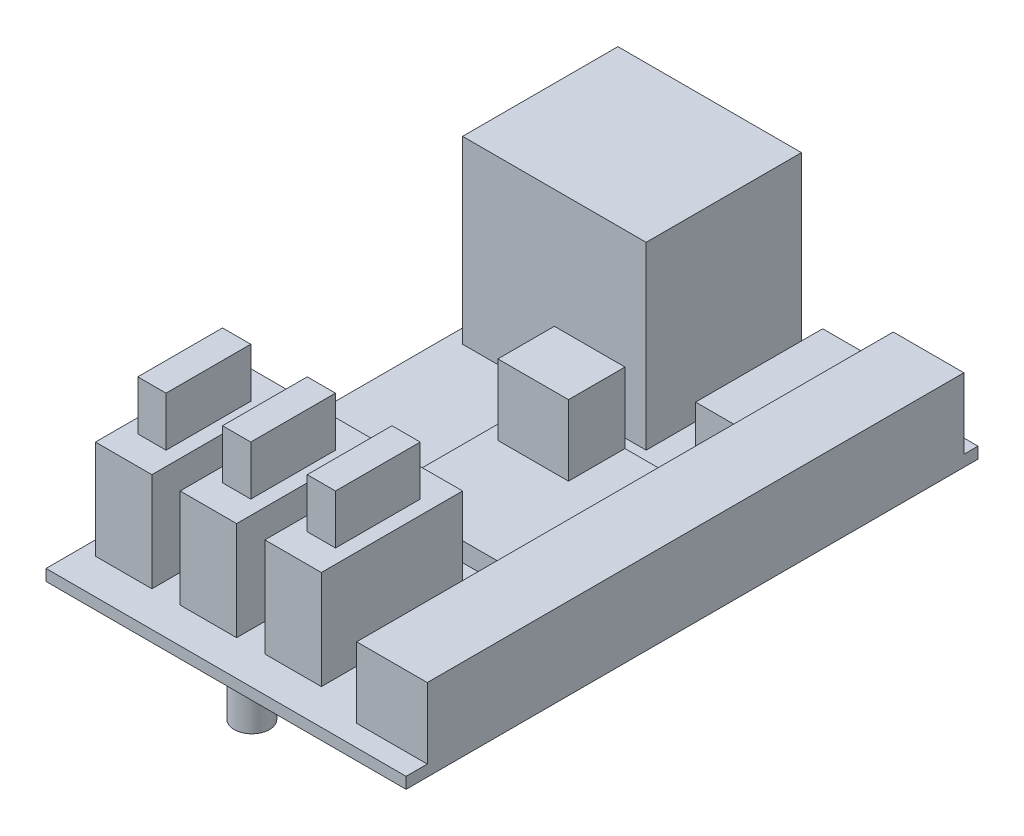
SolidWorks part; units mm, degrees
ref_plane "Front Plane" through (0, 0, 0) normal (0, 0, 1) x (1, 0, 0)
ref_plane "Top Plane" through (0, 0, 0) normal (0, 1, 0) x (1, 0, 0)
ref_plane "Right Plane" through (0, 0, 0) normal (1, 0, 0) x (0, 0, -1)
sketch "SK_P01_Standoff" plane through (0, 0, 0) normal (0, 1, 0) x (1, 0, 0)
  circle A0 centre (0, 36.85) radius 2.5
extrude "P01_Standoff" add sketch "SK_P01_Standoff" along normal blind 6
sketch "SK_P02_Standoff" plane through (0, 0, 0) normal (0, 1, 0) x (1, 0, 0)
  circle A0 centre (0, -36.85) radius 2.5
extrude "P02_Standoff" add sketch "SK_P02_Standoff" along normal blind 6
sketch "SK_P03_PermaProtohalfsizeboard" plane through (0, 0, 0) normal (0, 1, 0) x (1, 0, 0)
  line L0 (-25.5, -40.5) -> (25.5, -40.5)
  line L1 (25.5, -40.5) -> (25.5, 40.5)
  line L2 (25.5, 40.5) -> (-25.5, 40.5)
  line L3 (-25.5, 40.5) -> (-25.5, -40.5)
extrude "P03_PermaProtohalfsizeboard" add sketch "SK_P03_PermaProtohalfsizeboard" along normal blind 1.6 from offset 6
sketch "SK_P04_K1relayCB1aFP12V" plane through (0, 0, 0) normal (0, 1, 0) x (1, 0, 0)
  line L0 (-23.5, 16.5) -> (2.5, 16.5)
  line L1 (2.5, 16.5) -> (2.5, 38.5)
  line L2 (2.5, 38.5) -> (-23.5, 38.5)
  line L3 (-23.5, 38.5) -> (-23.5, 16.5)
extrude "P04_K1relayCB1aFP12V" add sketch "SK_P04_K1relayCB1aFP12V" along normal blind 25.5 from offset 7.6
sketch "SK_P05_R1D3D4K1coil" plane through (0, 0, 0) normal (0, 1, 0) x (1, 0, 0)
  line L0 (5.5, 20.5) -> (13.5, 20.5)
  line L1 (13.5, 20.5) -> (13.5, 38.5)
  line L2 (13.5, 38.5) -> (5.5, 38.5)
  line L3 (5.5, 38.5) -> (5.5, 20.5)
extrude "P05_R1D3D4K1coil" add sketch "SK_P05_R1D3D4K1coil" along normal blind 5.4 from offset 7.6
sketch "SK_P06_INA2601motor" plane through (0, 0, 0) normal (0, 1, 0) x (1, 0, 0)
  line L0 (-8.5, -10.3) -> (14.4, -10.3)
  line L1 (14.4, -10.3) -> (14.4, 12.5)
  line L2 (14.4, 12.5) -> (-8.5, 12.5)
  line L3 (-8.5, 12.5) -> (-8.5, -10.3)
extrude "P06_INA2601motor" add sketch "SK_P06_INA2601motor" along normal blind 2.7 from offset 7.6
sketch "SK_P07_INA260terminalblock" plane through (0, 0, 0) normal (0, 1, 0) x (1, 0, 0)
  line L0 (-6.5, 4.5) -> (3.5, 4.5)
  line L1 (3.5, 4.5) -> (3.5, 12.5)
  line L2 (3.5, 12.5) -> (-6.5, 12.5)
  line L3 (-6.5, 12.5) -> (-6.5, 4.5)
extrude "P07_INA260terminalblock" add sketch "SK_P07_INA260terminalblock" along normal blind 10 from offset 10.3
sketch "SK_P08_F1holder30APCBblade" plane through (0, 0, 0) normal (0, 1, 0) x (1, 0, 0)
  line L0 (-23.5, -35.5) -> (-15.5, -35.5)
  line L1 (-15.5, -35.5) -> (-15.5, -15.5)
  line L2 (-15.5, -15.5) -> (-23.5, -15.5)
  line L3 (-23.5, -15.5) -> (-23.5, -35.5)
extrude "P08_F1holder30APCBblade" add sketch "SK_P08_F1holder30APCBblade" along normal blind 14 from offset 7.6
sketch "SK_P09_F115Afuse" plane through (0, 0, 0) normal (0, 1, 0) x (1, 0, 0)
  line L0 (-21.5, -31.5) -> (-17.5, -31.5)
  line L1 (-17.5, -31.5) -> (-17.5, -19.5)
  line L2 (-17.5, -19.5) -> (-21.5, -19.5)
  line L3 (-21.5, -19.5) -> (-21.5, -31.5)
extrude "P09_F115Afuse" add sketch "SK_P09_F115Afuse" along normal blind 7 from offset 21.6
sketch "SK_P10_F3holder" plane through (0, 0, 0) normal (0, 1, 0) x (1, 0, 0)
  line L0 (-11.5, -35.5) -> (-3.5, -35.5)
  line L1 (-3.5, -35.5) -> (-3.5, -15.5)
  line L2 (-3.5, -15.5) -> (-11.5, -15.5)
  line L3 (-11.5, -15.5) -> (-11.5, -35.5)
extrude "P10_F3holder" add sketch "SK_P10_F3holder" along normal blind 14 from offset 7.6
sketch "SK_P11_F33Afuse" plane through (0, 0, 0) normal (0, 1, 0) x (1, 0, 0)
  line L0 (-9.5, -31.5) -> (-5.5, -31.5)
  line L1 (-5.5, -31.5) -> (-5.5, -19.5)
  line L2 (-5.5, -19.5) -> (-9.5, -19.5)
  line L3 (-9.5, -19.5) -> (-9.5, -31.5)
extrude "P11_F33Afuse" add sketch "SK_P11_F33Afuse" along normal blind 7 from offset 21.6
sketch "SK_P12_F4holder" plane through (0, 0, 0) normal (0, 1, 0) x (1, 0, 0)
  line L0 (0.5, -35.5) -> (8.5, -35.5)
  line L1 (8.5, -35.5) -> (8.5, -15.5)
  line L2 (8.5, -15.5) -> (0.5, -15.5)
  line L3 (0.5, -15.5) -> (0.5, -35.5)
extrude "P12_F4holder" add sketch "SK_P12_F4holder" along normal blind 14 from offset 7.6
sketch "SK_P13_F43Afuse" plane through (0, 0, 0) normal (0, 1, 0) x (1, 0, 0)
  line L0 (2.5, -31.5) -> (6.5, -31.5)
  line L1 (6.5, -31.5) -> (6.5, -19.5)
  line L2 (6.5, -19.5) -> (2.5, -19.5)
  line L3 (2.5, -19.5) -> (2.5, -31.5)
extrude "P13_F43Afuse" add sketch "SK_P13_F43Afuse" along normal blind 7 from offset 21.6
sketch "SK_P14_TerminalblocksTB1TB4wire" plane through (0, 0, 0) normal (0, 1, 0) x (1, 0, 0)
  line L0 (15.5, -37.5) -> (25.5, -37.5)
  line L1 (25.5, -37.5) -> (25.5, 38.5)
  line L2 (25.5, 38.5) -> (15.5, 38.5)
  line L3 (15.5, 38.5) -> (15.5, -37.5)
extrude "P14_TerminalblocksTB1TB4wire" add sketch "SK_P14_TerminalblocksTB1TB4wire" along normal blind 10 from offset 7.6
